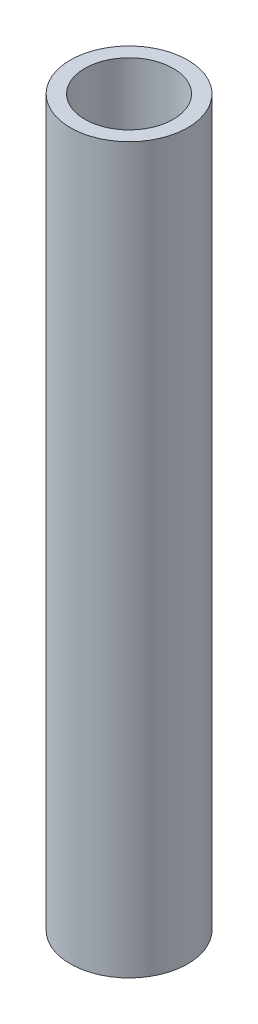
SolidWorks part; units mm, degrees
ref_plane "Płaszczyzna przednia" through (0, 0, 0) normal (0, 0, 1) x (1, 0, 0)
ref_plane "Płaszczyzna górna" through (0, 0, 0) normal (0, 1, 0) x (1, 0, 0)
ref_plane "Płaszczyzna prawa" through (0, 0, 0) normal (1, 0, 0) x (0, 0, -1)
sketch "Szkic1" plane through (0, 0, 0) normal (0, 1, 0) x (1, 0, 0)
  circle A0 centre (0, 0) radius 12.7
  circle A1 centre (0, 0) radius 16.85
  dimension "D1" = 25.4
  dimension "D2" = 33.7
extrude "Dodanie-wyciągnięcie1" add sketch "Szkic1" along normal blind 208
